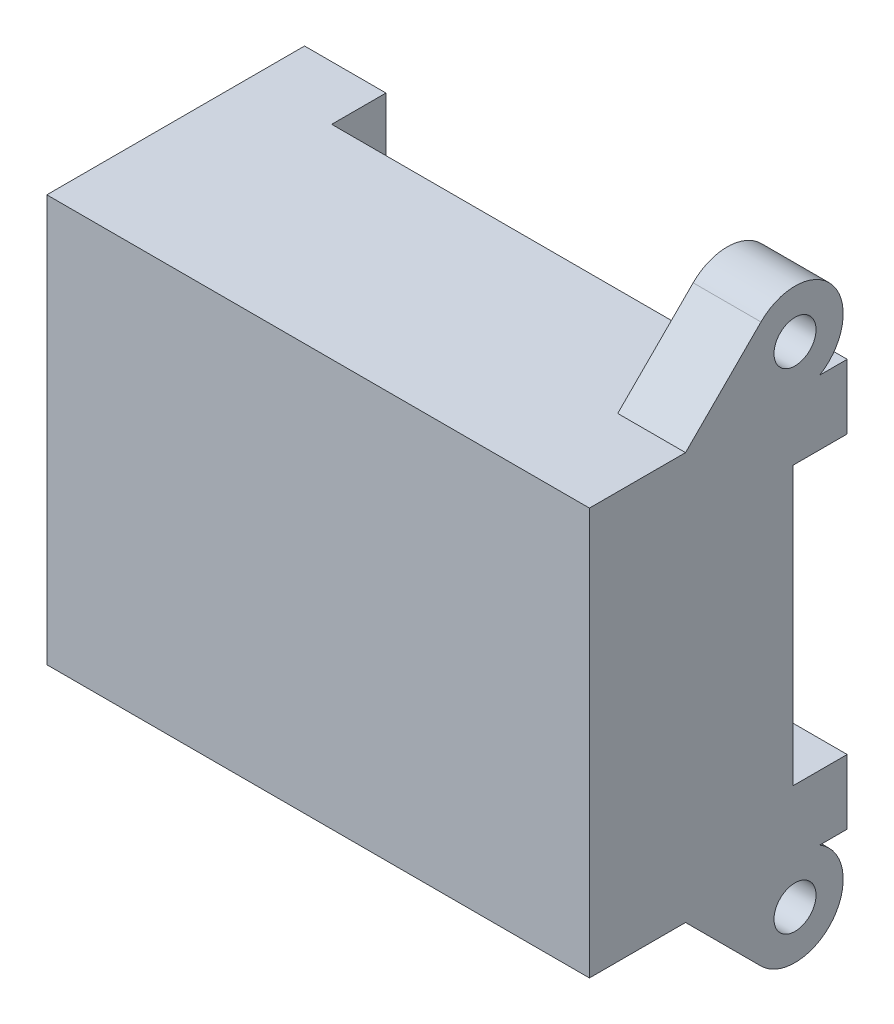
SolidWorks part; units mm, degrees
ref_plane "前视基准面" through (0, 0, 0) normal (0, 0, 1) x (1, 0, 0)
ref_plane "上视基准面" through (0, 0, 0) normal (0, 1, 0) x (1, 0, 0)
ref_plane "右视基准面" through (0, 0, 0) normal (1, 0, 0) x (0, 0, -1)
sketch "草图1" plane through (0, 0, 0) normal (0, 0, 1) x (1, 0, 0)
  line L0 (-29.15, 4.6184) -> (-29.15, -3.6184) construction
  line L1 (-84.15, 15.5) -> (-44.15, 15.5)
  line L2 (-84.15, 15.5) -> (-84.15, -14.5)
  line L3 (-84.15, -14.5) -> (-44.15, -14.5)
  line L4 (-44.15, 15.5) -> (-44.15, -14.5)
  line L6 (-148.2, 0.5) -> (-38.212, 0.5) construction
  line L7 (-148.2, 10.23) -> (-148.2, -9.23) construction
  point P6 (-38.212, 0.5)
  dimension "D1" = 40
  dimension "D2" = 30
  dimension "D3" = 15
extrude "凸台-拉伸1" add sketch "草图1" against normal up to surface (15 mm away)
sketch "草图3" plane through (-44.15, 0, 0) normal (1, 0, 0) x (0, 0, -1)
  line L1 (21.7736, 17) -> (10.0505, 17) construction
  line L2 (15, 15.5) -> (0, 15.5) construction
  line L3 (15.155, 23.504) -> (15.155, 11.8832) construction
  line L4 (12.6448, 21.0602) -> (7.0845, 15.5)
  line L8 (15, 10.23) -> (15, -9.23)
  line L9 (15, -9.23) -> (15.31, -9.23)
  line L10 (15.31, -9.23) -> (15.31, 10.23)
  line L11 (15.31, 10.23) -> (15, 10.23)
  line L12 (15, 10.23) -> (15, -9.23) construction
  line L13 (15, -9.23) -> (15.31, -9.23) construction
  line L14 (15.31, -9.23) -> (15.31, 10.23) construction
  line L15 (15.31, 10.23) -> (15, 10.23) construction
  circle A0 centre (15.155, 18.55) radius 1.55
  circle A1 centre (15.155, 18.55) radius 3.55
  point P11 (0, 0)
  point P18 (15, 22.6322)
  dimension "D1" = 3.1
  dimension "D2" = 2
  dimension "D3" = 1.5
  dimension "D5" = 45
  dimension "D4" = 0
extrude "凸台-拉伸2" add sketch "草图3" against normal blind 5
ref_plane "基准面-中间" through (0, 0.5, 0) normal (0, 1, 0) x (1, 0, 0)
mirror "镜向2" about plane through (0, 0.5, 0) normal (0, 1, 0) of "凸台-拉伸2"
sketch "草图4" plane through (0, 0, -15) normal (0, 0, -1) x (-1, 0, 0)
  line L0 (44.15, -14.0034) -> (44.15, 15.0034) construction
  line L1 (44.15, 10.73) -> (50.15, 10.73)
  line L2 (44.15, 10.73) -> (44.15, 15.5)
  line L3 (44.15, 15.5) -> (50.15, 15.5)
  line L4 (50.15, 10.73) -> (50.15, 15.5)
  line L5 (49.15, 15.5) -> (84.15, 15.5) construction
  line L6 (30.5, 10.23) -> (48.15, 10.23) construction
  line L7 (84.15, -14.5) -> (49.15, -14.5) construction
  line L8 (84.15, 15.5) -> (78.15, 15.5)
  line L9 (84.15, 15.5) -> (84.15, 10.73)
  line L10 (84.15, 10.73) -> (78.15, 10.73)
  line L11 (78.15, 15.5) -> (78.15, 10.73)
  line L12 (84.15, -14.5) -> (78.15, -14.5)
  line L13 (84.15, -14.5) -> (84.15, -9.73)
  line L14 (84.15, -9.73) -> (78.15, -9.73)
  line L15 (78.15, -14.5) -> (78.15, -9.73)
  line L16 (44.15, -9.73) -> (50.15, -9.73)
  line L17 (44.15, -9.73) -> (44.15, -14.5)
  line L18 (44.15, -14.5) -> (50.15, -14.5)
  line L19 (50.15, -9.73) -> (50.15, -14.5)
  line L20 (30.5, -9.23) -> (48.15, -9.23) construction
  line L21 (83.25, -9.23) -> (84.15, -9.23) construction
  line L22 (83.25, 10.23) -> (84.15, 10.23) construction
  dimension "D1" = 0.5
  dimension "D2" = 6
  dimension "D3" = 0.5
  dimension "D4" = 0.5
  dimension "D5" = 0.5
  dimension "D6" = 6
  dimension "D7" = 6
  dimension "D8" = 6
extrude "凸台-拉伸3" add sketch "草图4" along normal blind 4
